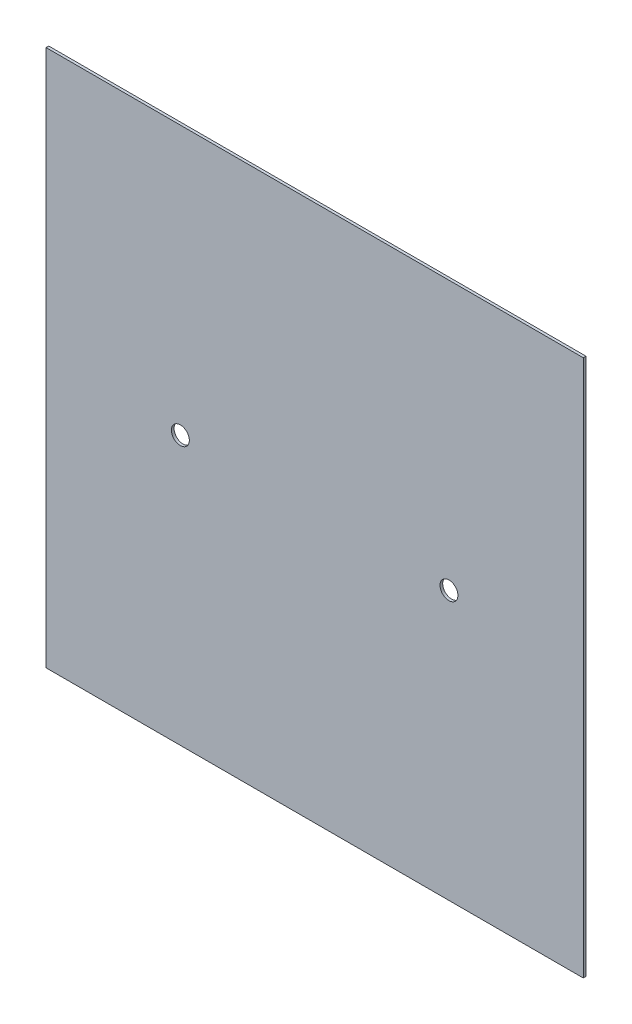
SolidWorks part; units mm, degrees
ref_plane "Front Plane" through (0, 0, 0) normal (0, 0, 1) x (1, 0, 0)
ref_plane "Top Plane" through (0, 0, 0) normal (0, 1, 0) x (1, 0, 0)
ref_plane "Right Plane" through (0, 0, 0) normal (1, 0, 0) x (0, 0, -1)
sketch "Sketch2" plane through (0, 0, 0) normal (0, 0, 1) x (1, 0, 0)
  line L0 (-150, 0) -> (150, 0) construction
  line L1 (-150, 150) -> (150, 150)
  line L2 (-150, 150) -> (-150, -150)
  line L3 (-150, -150) -> (150, -150)
  line L4 (150, 150) -> (150, -150)
  line L5 (-150, 150) -> (150, -150) construction
  line L6 (-150, -150) -> (150, 150) construction
  circle A0 centre (-75, 0) radius 5
  circle A1 centre (75, 0) radius 5
  point P0 (0, 0)
  point P9 (0, 0)
  point P13 (0, 0)
  point P14 (0, 0)
  dimension "D3" = 75
  dimension "D5" = 10
  dimension "D6" = 10
  dimension "D1" = 300
  dimension "D2" = 300
  dimension "D4" = 75
  dimension "D7" = 150
extrude "Boss-Extrude1" add sketch "Sketch2" along normal blind 1.5
